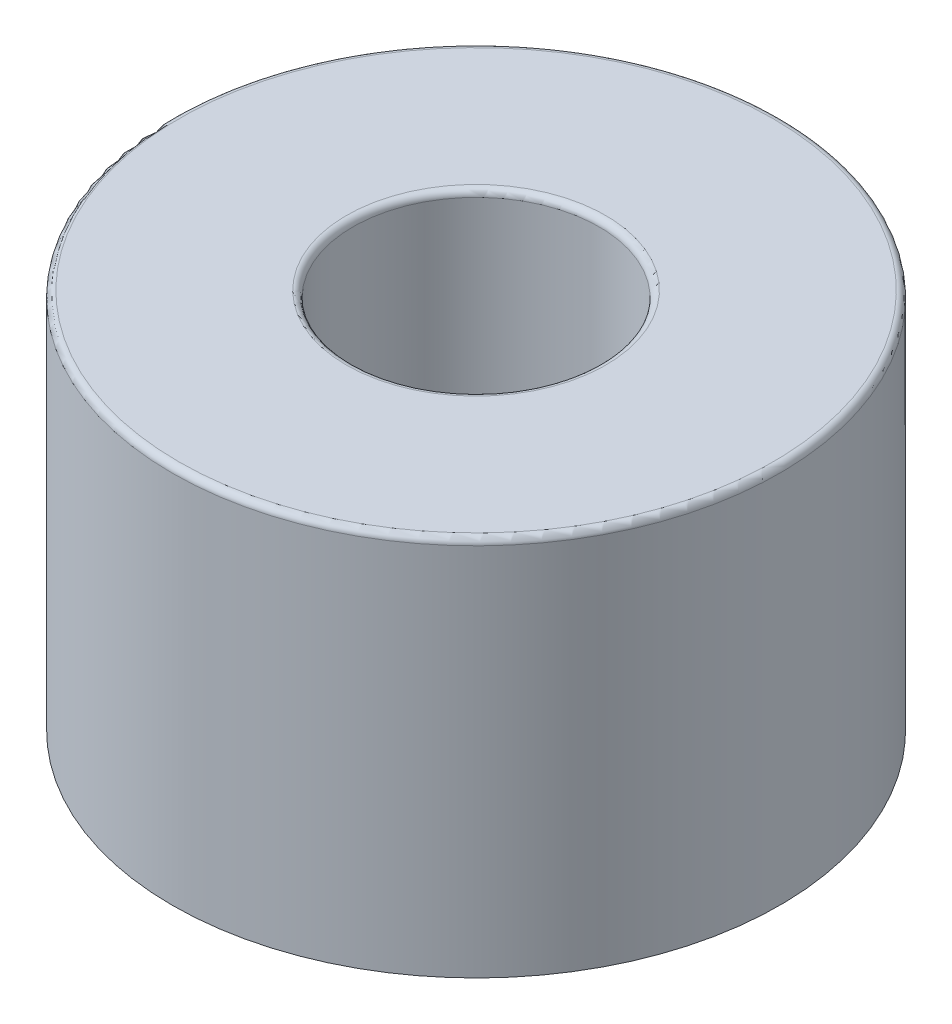
SolidWorks part; units mm, degrees
material "POLYURETHANE (11671)"
ref_plane "Front" through (0, 0, 0) normal (0, 0, 1) x (1, 0, 0)
ref_plane "Top" through (0, 0, 0) normal (0, 1, 0) x (1, 0, 0)
ref_plane "Right" through (0, 0, 0) normal (1, 0, 0) x (0, 0, -1)
sketch "Sketch1" plane through (0, 0, 0) normal (0, 1, 0) x (1, 0, 0)
  circle A0 centre (0, 0) radius 4.7625
  circle A1 centre (0, 0) radius 11.75
  dimension "D1" = 9.525
  dimension "D2" = 23.5
extrude "Boss-Extrude1" add sketch "Sketch1" along normal blind 14.732
fillet "Fillet1" radius 0.254 2 edges at (0, 14.732, 4.7625) (0, 14.732, 11.75)
